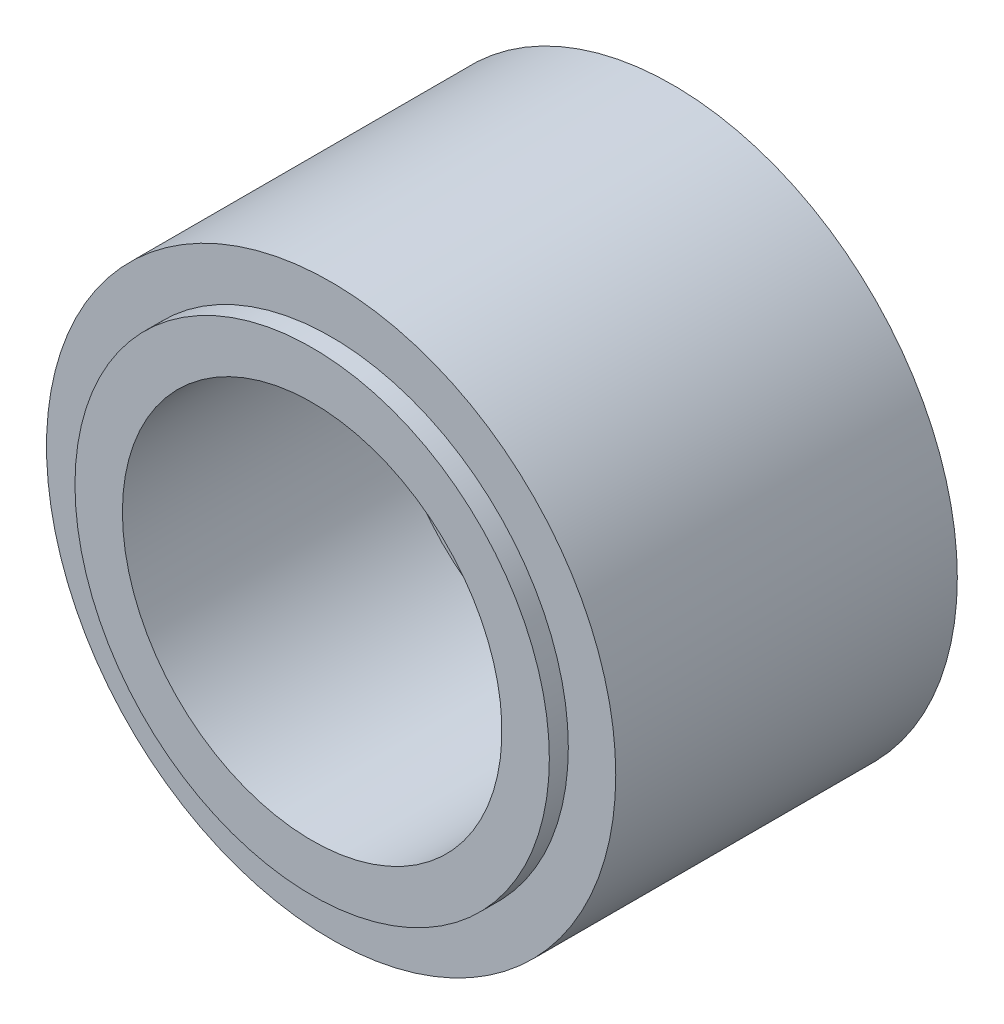
SolidWorks part; units mm, degrees
ref_plane "Alzado" through (0, 0, 0) normal (0, 0, 1) x (1, 0, 0)
ref_plane "Planta" through (0, 0, 0) normal (0, 1, 0) x (1, 0, 0)
ref_plane "Vista lateral" through (0, 0, 0) normal (1, 0, 0) x (0, 0, -1)
sketch "Croquis1" plane through (0, 0, 0) normal (1, 0, 0) x (0, 0, -1)
  line L0 (0, -1.5) -> (0, -12.5)
  line L1 (0, -12.5) -> (-1, -12.5)
  line L2 (-1, -12.5) -> (-1, -11)
  line L3 (-1, -11) -> (-19, -11)
  line L4 (-19, -11) -> (-19, -12.5)
  line L5 (-19, -12.5) -> (-20, -12.5)
  line L6 (-20, -12.5) -> (-20, -10)
  line L7 (-20, -10) -> (-6, -10)
  line L8 (-6, -10) -> (-6, -1.5)
  line L9 (0, -1.5) -> (-6, -1.5)
  line L10 (0, 0) -> (-20, 0) construction
  dimension "D1" = 1.5
  dimension "D2" = 10
  dimension "D3" = 12.5
  dimension "D4" = 18
  dimension "D5" = 1
  dimension "D6" = 1
  dimension "D7" = 1
  dimension "D8" = 6
  dimension "D9" = 11
revolve "Revolución1" add sketch "Croquis1" angle 360 about L10
ref_plane "Plano1" through (0, 0, 1) normal (0, 0, 1) x (1, 0, 0)
sketch "Croquis2" plane through (0, 0, 1) normal (0, 0, 1) x (1, 0, 0)
  circle A0 centre (0, 0) radius 15
  circle A1 centre (0, 0) radius 12.5 construction
  circle A2 centre (0, 0) radius 12.5
  dimension "D1" = 30
extrude "Saliente-Extruir1" add sketch "Croquis2" along normal up to surface (18 mm away) up to face at (-11, 0, 19)
